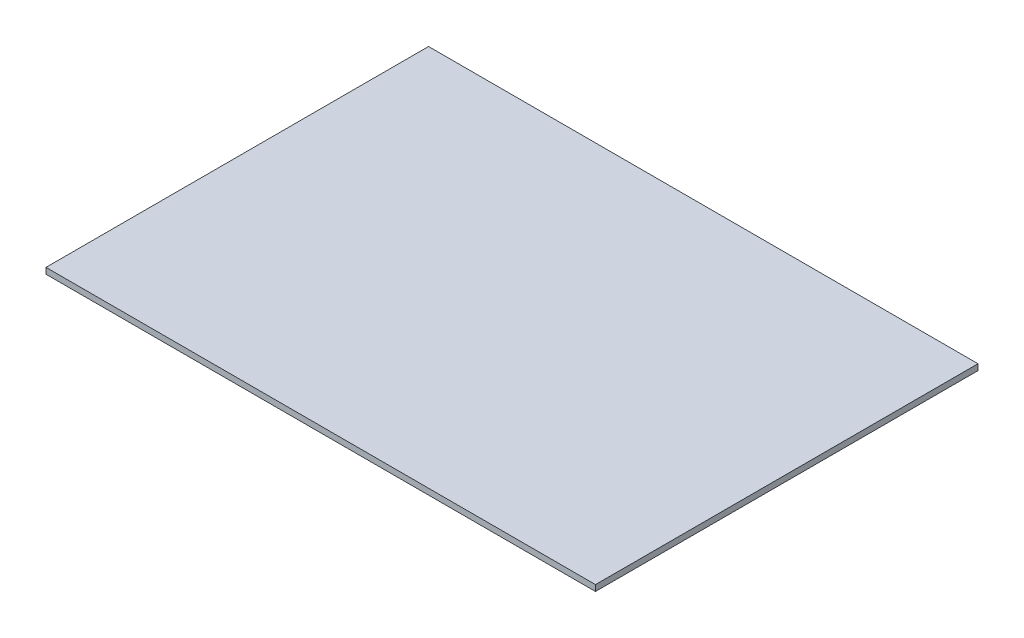
SolidWorks part; units mm, degrees
ref_plane "Front Plane" through (0, 0, 0) normal (0, 0, 1) x (1, 0, 0)
ref_plane "Top Plane" through (0, 0, 0) normal (0, 1, 0) x (1, 0, 0)
ref_plane "Right Plane" through (0, 0, 0) normal (1, 0, 0) x (0, 0, -1)
sketch "Sketch1" plane through (0, 0, 0) normal (0, 1, 0) x (1, 0, 0)
  line L1 (0, 0) -> (165.1, 0)
  line L2 (0, 0) -> (0, 114.94)
  line L3 (0, 114.94) -> (165.1, 114.94)
  line L4 (165.1, 0) -> (165.1, 114.94)
  dimension "D1" = 165.1
  dimension "D2" = 114.94
extrude "Extrude1" add sketch "Sketch1" against normal blind 1.8
sketch "Sketch2" plane through (0, 0, 0) normal (0, 1, 0) x (1, 0, 0)
  circle A0 centre (5.08, 5.08) radius 1.5875
  point P0 (5.08, 5.08)
  point P1 (5.08, 109.86)
  point P2 (160.02, 109.86)
  point P3 (160.02, 5.08)
  point P4 (71.12, 109.86)
  point P5 (144.78, 109.86)
  point P6 (147.32, 24.13)
  point P7 (67.91, 24.13)
  dimension "D10" = 3.175
  dimension "D1" = 5.08
  dimension "D2" = 5.08
  dimension "D3" = 109.86
  dimension "D4" = 160.02
  dimension "D5" = 71.12
  dimension "D6" = 144.78
  dimension "D7" = 67.91
  dimension "D8" = 24.13
  dimension "D9" = 147.32
extrude "Extrude2" [suppressed] cut sketch "Sketch2" against normal through all
pattern_sketch "Sketch-Pattern1" [suppressed]
